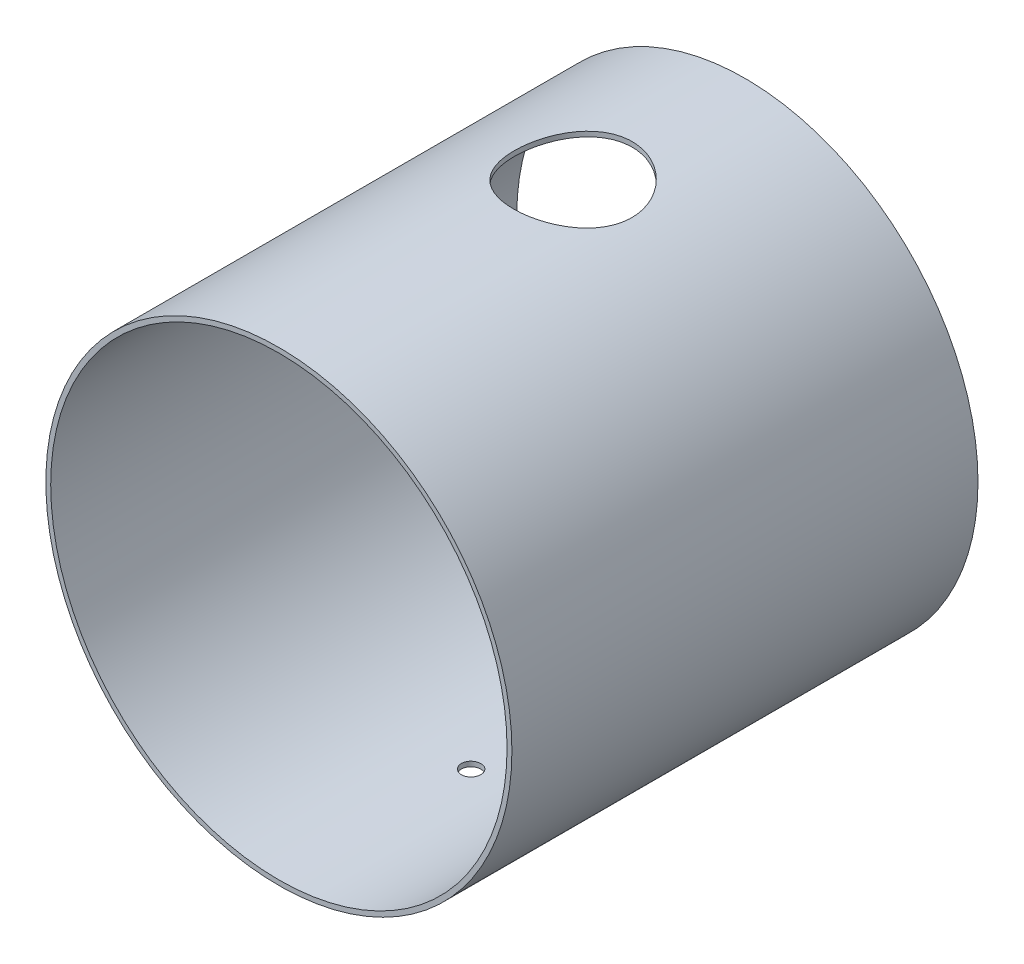
SolidWorks part; units mm, degrees
ref_plane "Front Plane" through (0, 0, 0) normal (0, 0, 1) x (1, 0, 0)
ref_plane "Top Plane" through (0, 0, 0) normal (0, 1, 0) x (1, 0, 0)
ref_plane "Right Plane" through (0, 0, 0) normal (1, 0, 0) x (0, 0, -1)
sketch "Sketch1" plane through (0, 0, 0) normal (0, 0, 1) x (1, 0, 0)
  line L0 (-149.225, 0) -> (-152.4, 0) construction
  circle A0 centre (0, 0) radius 149.225
  circle A1 centre (0, 0) radius 152.4
  dimension "OD" = 304.8
  dimension "ID" = 298.45
  dimension "Wall Thickness" = 3.175
sketch "Sketch2" plane through (0, 0, 0) normal (1, 0, 0) x (0, 0, -1)
  line L0 (-152.4, -152.4) -> (152.4, -152.4)
  line L1 (-76.2, 152.4) -> (76.2, 152.4) construction
  line L3 (-152.4, 152.4) -> (152.4, 152.4)
  point P2 (0, -152.4)
  point P3 (0, 152.4)
  point P10 (-76.2, 152.4)
  point P12 (76.2, 152.4)
  dimension "Length" = 304.8
  dimension "OD" = 304.8
  dimension "D1" = 152.4
sketch "Sketch3" plane through (0, 0, 0) normal (0, 0, 1) x (1, 0, 0)
  circle A0 centre (0, 0) radius 149.225 construction
  circle A1 centre (0, 0) radius 152.4 construction
  circle A2 centre (0, 0) radius 149.225
  circle A3 centre (0, 0) radius 152.4
extrude "Boss-Extrude1" add sketch "Sketch3" along normal mid plane 304.8
hole_wizard "Ø1.0mm Dowel Hole1" positions "3DSketch1" profile "Sketch4" hole size "Ø1.0" standard "ANSI Metric"
sketch3d "3DSketch1"
  point P0 (-1.2376, 152.395, -41.1956)
  point P1 (-1.2376, 152.395, -41.1956)
  point P3 (-1.2376, 152.395, -41.1956)
  point P4 (-7.5194, 152.2144, -47.4786)
  point P5 (-7.6448, 152.2081, -41.0699)
  point P6 (-1.2376, 152.395, -41.1956)
sketch "Sketch4" plane through (-1.2376, 152.395, -41.1956) normal (0, 0, 1) x (-1, -0.0081, 0)
  line L0 (0, 0) -> (0, 3.175)
  line L1 (0, 3.175) -> (38.5, 3.175)
  line L2 (38.5, 3.175) -> (38.5, 0)
  line L5 (38.5, 0) -> (0, 0)
  line L11 (0, -6.35) -> (0, 107.95) construction
  dimension "Thru Hole Dia." = 77
  dimension "Thru Hole Depth" = 3.175
hole_wizard "1/2 (0.5) Diameter Hole1" positions "3DSketch2" profile "Sketch5" hole size "1/2" standard "ANSI Inch"
sketch3d "3DSketch2"
  point P0 (-0.5472, -152.399, -42.1363)
  point P2 (0.1824, -152.3999, 26.814)
sketch "Sketch5" plane through (-0.5472, -152.399, -42.1363) normal (0, 0, 1) x (1, -0.0036, 0)
  line L0 (0, 0) -> (0, 3.175)
  line L1 (0, 3.175) -> (6.35, 3.175)
  line L2 (6.35, 3.175) -> (6.35, 0)
  line L5 (6.35, 0) -> (0, 0)
  line L11 (0, -6.35) -> (0, 107.95) construction
  dimension "Thru Hole Dia." = 12.7
  dimension "Thru Hole Depth" = 3.175
equation "\"D1@Boss-Extrude1\"=\"length@sketch2\""
equation "\"D1@Sketch2\"=\"Length@Sketch2\"*0.5"
